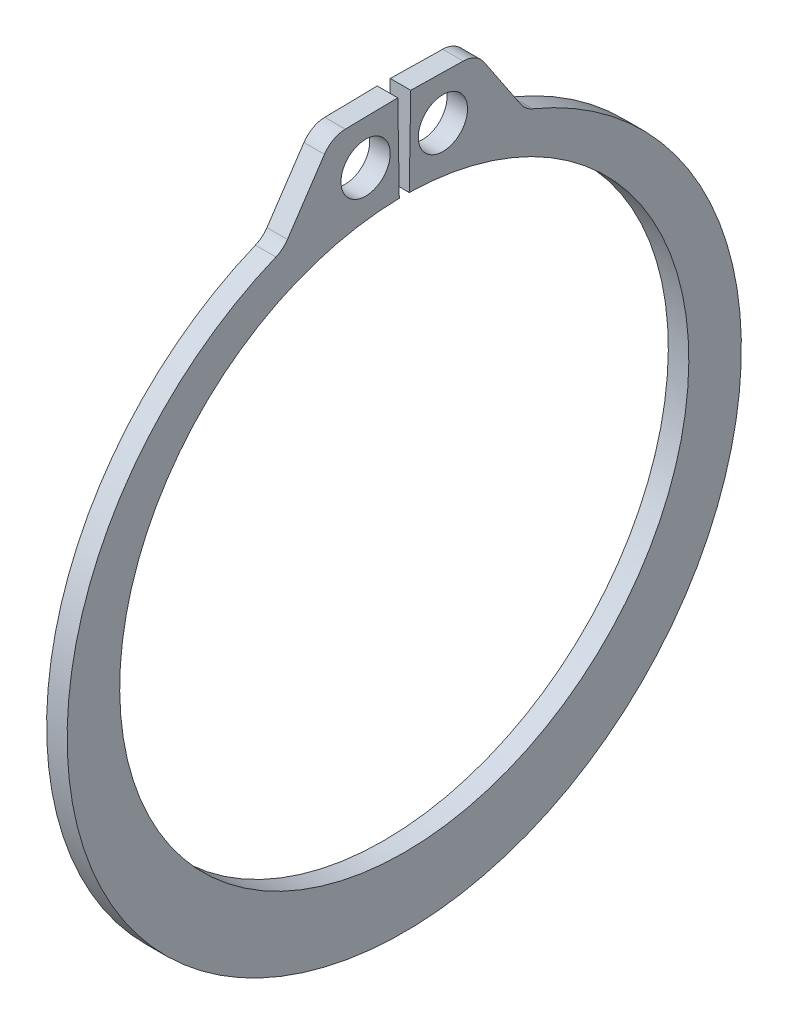
SolidWorks part; units mm, degrees
material "Cast Carbon Steel"
ref_plane "Front" through (0, 0, 0) normal (0, 0, 1) x (1, 0, 0)
ref_plane "Top" through (0, 0, 0) normal (0, 1, 0) x (1, 0, 0)
ref_plane "Right" through (0, 0, 0) normal (1, 0, 0) x (0, 0, -1)
sketch "Sketch1" plane through (0, 0, 0) normal (1, 0, 0) x (0, 0, -1)
  line L0 (0, 0) -> (0, 17.6149) construction
  line L1 (-0.3074, 17.6122) -> (-0.4023, 23.047)
  line L2 (0.4023, 23.047) -> (4.4784, 22.9758)
  line L3 (4.4784, 22.9758) -> (7.5032, 18.4597)
  line L4 (0.3074, 17.6122) -> (0.4023, 23.047)
  line L5 (-0.4023, 23.047) -> (-4.4784, 22.9758)
  line L6 (-4.4784, 22.9758) -> (-7.5032, 18.4597)
  line L7 (-7.5032, 18.4597) -> (-6.6329, 16.3184) construction
  line L8 (7.5032, 18.4597) -> (6.6329, 16.3184) construction
  line L9 (0, -17.6149) -> (0, -21.8821) construction
  line L10 (-4.4784, 22.9758) -> (-0.3074, 17.6122) construction
  line L11 (0, 17.6149) -> (0, 23.0505) construction
  line L12 (-17.6149, 0) -> (17.6149, 0) construction
  circle A0 centre (0, 0) radius 17.6149 construction
  arc A1 (-0.3074, 17.6122) -> (0.3074, 17.6122) centre (0, 0) ccw
  circle A3 centre (0, 0) radius 24.7015 construction
  circle A4 centre (-2.3929, 20.294) radius 1.524
  circle A5 centre (2.3929, 20.294) radius 1.524
  arc A6 (-7.5032, 18.4597) -> (7.5032, 18.4597) centre (0, -1.0135) ccw
  point P0 (0, -21.8821)
  dimension "A" = 35.2298
  dimension "Hole" = 3.048
  dimension "Smin" = 2.3114
  dimension "H" = 5.4356
  dimension "D2" = 4.0767
  dimension "Angle" = 1
extrude "Extrude1" add sketch "Sketch1" along normal mid plane 1.27
fillet "Fillet1" radius 1.5875 4 edges at (0, 18.4597, 7.5032) (0, 18.4597, -7.5032) (0, 22.9758, 4.4784) (0, 22.9758, -4.4784)
sketch "Sketch2" plane through (0, 0, 0) normal (0, 0, 1) x (1, 0, 0)
  line L0 (-7.0612, 0) -> (18.3388, 0)
  line L1 (18.3388, 0) -> (18.3388, -19.05)
  line L2 (-0.7112, -19.05) -> (-5.8674, -19.05)
  line L3 (18.3388, -19.05) -> (0.7112, -19.05)
  line L4 (0.7112, -19.05) -> (0.7112, -17.8562)
  line L5 (0.7112, -17.8562) -> (-0.7112, -17.8562)
  line L6 (-0.7112, -17.8562) -> (-0.7112, -19.05)
  line L7 (-0.7112, -19.05) -> (-7.0612, -19.05) construction
  line L8 (-7.0612, -19.05) -> (-7.0612, 0) construction
  line L9 (18.3388, 0) -> (76.391, 0) construction
  line L10 (-5.8674, -19.05) -> (-7.0612, -17.8562)
  line L11 (-7.0612, -17.8562) -> (-7.0612, 0)
  point P10 (0, -17.8562)
  dimension "D2" = 25.4
  dimension "D3" = 6.35
  dimension "D1" = 45
revolve "Revolve1" [suppressed] add sketch "Sketch2" angle 360 about L9
delete or keep bodies "Body-Delete1" [suppressed] type delete bodies bodies 122
equation "\"D2@Sketch2\" = \"D1@Extrude1\"*20"
equation "\"D3@Sketch2\" = \"D2@Sketch2\"/4"
equation "\"D2@Sketch1\" = \"H@Sketch1\"*.75"
